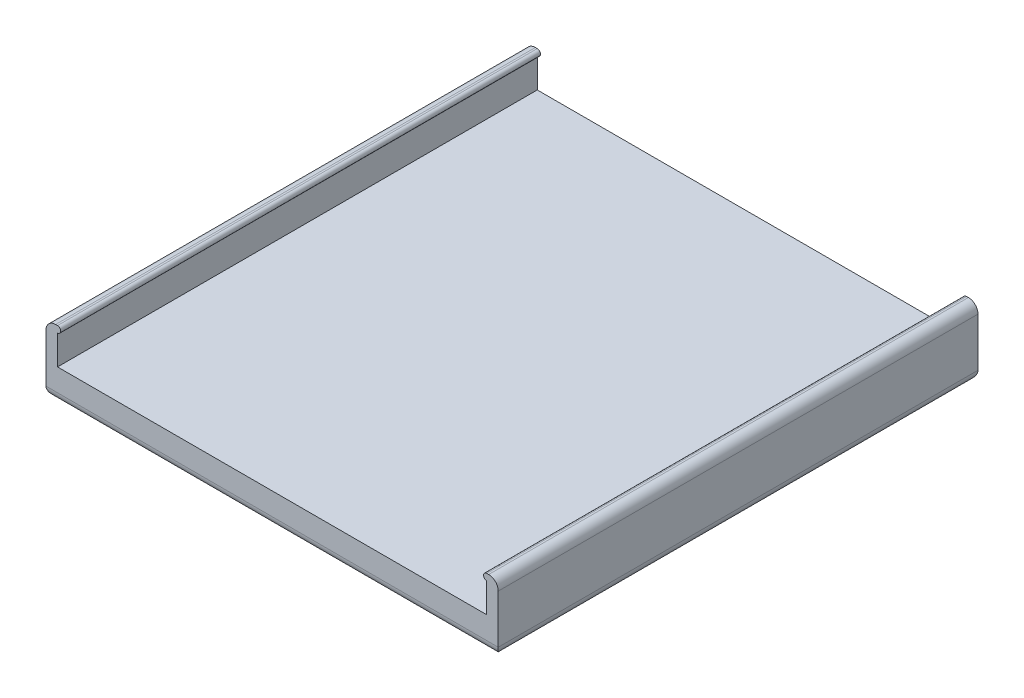
SolidWorks part; units mm, degrees
ref_plane "Front Plane" through (0, 0, 0) normal (0, 0, 1) x (1, 0, 0)
ref_plane "Top Plane" through (0, 0, 0) normal (0, 1, 0) x (1, 0, 0)
ref_plane "Right Plane" through (0, 0, 0) normal (1, 0, 0) x (0, 0, -1)
sketch "Sketch1" plane through (0, 0, 0) normal (0, 1, 0) x (1, 0, 0)
  line L1 (36.25, -37.5) -> (-36.25, -37.5)
  line L2 (36.25, -37.5) -> (36.25, 37.5)
  line L3 (36.25, 37.5) -> (-36.25, 37.5)
  line L4 (-36.25, -37.5) -> (-36.25, 37.5)
  line L5 (36.25, -37.5) -> (-36.25, 37.5) construction
  line L6 (36.25, 37.5) -> (-36.25, -37.5) construction
  point P0 (0, 0)
  dimension "D1" = 75
  dimension "D2" = 72.5
extrude "Boss-Extrude1" add sketch "Sketch1" along normal blind 5
sketch "Sketch2" plane through (0, 0, 0) normal (0, -1, 0) x (1, 0, 0)
  circle A0 centre (0, 0) radius 25.1
  circle A1 centre (0, 0) radius 27.1
  dimension "D1" = 50.2
  dimension "D2" = 2
extrude "Boss-Extrude2" add sketch "Sketch2" along normal blind 5
ref_plane "Plane1" through (0, 0, 0) normal (1, 0, 0) x (0, 0, -1)
sketch "Sketch3" plane through (0, 0, 0) normal (1, 0, 0) x (0, 0, -1)
  line L0 (0, 0) -> (0, -1)
  line L1 (0, -1) -> (-25.05, -1)
  circle A0 centre (-25.05, -1) radius 0.5
  dimension "D2" = 1
  dimension "D1" = 25.05
  dimension "D3" = 1
sketch "Sketch4" plane through (0, 5, 0) normal (0, 1, 0) x (1, 0, 0)
  line L0 (36.25, 37.5) -> (-36.25, 37.5) construction
  line L1 (-36.25, -37.5) -> (-33.55, -37.5)
  line L2 (-36.25, -37.5) -> (-36.25, 37.5)
  line L3 (-36.25, 37.5) -> (-33.55, 37.5)
  line L4 (-33.55, -37.5) -> (-33.55, 37.5)
  line L6 (36.25, -37.5) -> (33.55, -37.5)
  line L7 (36.25, -37.5) -> (36.25, 37.5)
  line L8 (36.25, 37.5) -> (33.55, 37.5)
  line L9 (33.55, -37.5) -> (33.55, 37.5)
  dimension "D1" = 2.7
extrude "Boss-Extrude3" add sketch "Sketch4" along normal blind 5.6
sketch "Sketch5" plane through (0, 0, 37.5) normal (0, 0, 1) x (1, 0, 0)
  line L0 (-33.55, 10.6) -> (-33.55, 10.1) construction
  line L1 (-33.55, 10.6) -> (-33.55, 5) construction
  line L2 (-33.55, 10.1) -> (33.55, 10.1) construction
  line L3 (33.55, 10.6) -> (33.55, 5) construction
  circle A0 centre (-33.55, 10.1) radius 0.5
  circle A1 centre (33.55, 10.1) radius 0.5
  dimension "D1" = 1
  dimension "D2" = 0.5
extrude "Boss-Extrude4" add sketch "Sketch5" against normal up to surface (75 mm away) up to face at (0, 6.55, -37.5)
sketch "Sketch6" plane through (0, 0, -37.5) normal (0, 0, -1) x (-1, 0, 0)
  line L0 (-36.25, 0) -> (36.25, 0) construction
  line L1 (-36.25, 10.6) -> (-35.35, 10.6)
  line L2 (-36.25, 10.6) -> (-36.25, 0)
  line L3 (-36.25, 0) -> (-35.35, 0)
  line L4 (-35.35, 10.6) -> (-35.35, 0)
  line L5 (33.55, 10.6) -> (36.25, 10.6) construction
  line L6 (36.25, 0) -> (35.35, 0)
  line L7 (36.25, 0) -> (36.25, 10.6)
  line L8 (36.25, 10.6) -> (35.35, 10.6)
  line L9 (35.35, 0) -> (35.35, 10.6)
  line L10 (-33.55, 9.6) -> (-33.55, 5) construction
  line L11 (33.55, 9.6) -> (33.55, 5) construction
  dimension "D1" = 1.8
  dimension "D2" = 1.8
extrude "Cut-Extrude1" cut sketch "Sketch6" against normal through all
fillet "Fillet1" radius 2 1 edges at (0, 0, 27.1)
fillet "Fillet2" radius 1 1 edges at (0, -5, -25.1)
fillet "Fillet3" radius 1.5 4 edges at (0, 0, -37.5) (0, 0, 37.5) (-35.35, 0, 0) (35.35, 0, 0)
fillet "Fillet4" radius 1.5 2 edges at (35.35, 10.6, 0) (-35.35, 10.6, 0)
revolve "Revolve1" add sketch "Sketch3" angle 360 about L0
